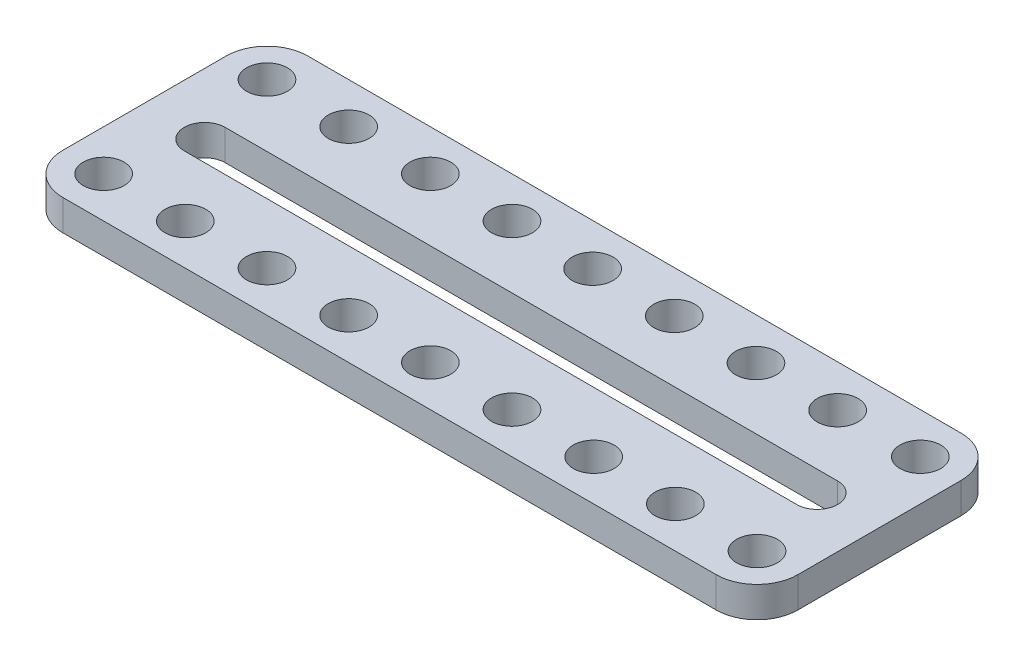
SolidWorks part; units mm, degrees
other "Markup1"
sketch "Sketch2" plane through (-43.3579, 0, 0.181) normal (0, 1, 0) x (1, 0, 0)
material "6061 Alloy"
ref_plane "前视基准面" through (0, 0, 0) normal (0, 0, 1) x (1, 0, 0)
ref_plane "上视基准面" through (0, 0, 0) normal (0, 1, 0) x (1, 0, 0)
ref_plane "右视基准面" through (0, 0, 0) normal (1, 0, 0) x (0, 0, -1)
other "Configuration Table"
sketch "Sketch11" plane through (0, 0, 0) normal (0, 1, 0) x (1, 0, 0)
  line L0 (-55.7524, -4.8796) -> (-55.7524, -20.8796)
  line L1 (-51.7524, -24.8796) -> (12.2476, -24.8796)
  line L2 (16.2476, -20.8796) -> (16.2476, -4.8796)
  line L3 (12.2476, -0.8796) -> (-51.7524, -0.8796)
  arc A0 (12.2476, -24.8796) -> (16.2476, -20.8796) centre (12.2476, -20.8796) ccw
  arc A1 (16.2476, -4.8796) -> (12.2476, -0.8796) centre (12.2476, -4.8796) ccw
  arc A2 (-55.7524, -20.8796) -> (-51.7524, -24.8796) centre (-51.7524, -20.8796) ccw
  arc A3 (-55.7524, -4.8796) -> (-51.7524, -0.8796) centre (-51.7524, -4.8796) cw
  dimension "D1" = 4
sketch "Sketch12" plane through (0, 0, 0) normal (0, 1, 0) x (1, 0, 0)
  line L0 (10.2476, -12.9827) -> (-49.7524, -12.9827) construction
  line L1 (10.2476, -14.9827) -> (-49.7524, -14.9827)
  line L2 (10.2476, -10.9827) -> (-49.7524, -10.9827)
  line L3 (-55.7524, -4.8796) -> (-55.7524, -20.8796) construction
  circle A0 centre (-51.7524, -4.8796) radius 2
  circle A1 centre (-43.7524, -4.8796) radius 2
  circle A2 centre (-35.7524, -4.8796) radius 2
  circle A3 centre (-27.7524, -4.8796) radius 2
  circle A4 centre (-19.7531, -4.9827) radius 2
  circle A5 centre (-11.7531, -4.9827) radius 2
  circle A6 centre (-3.7531, -4.9827) radius 2
  circle A7 centre (4.2469, -4.9827) radius 2
  circle A8 centre (12.2476, -4.8796) radius 2
  circle A9 centre (-51.7524, -20.8796) radius 2
  circle A10 centre (-43.7524, -20.8796) radius 2
  circle A11 centre (-35.7524, -20.8796) radius 2
  circle A12 centre (-27.7524, -20.8796) radius 2
  circle A13 centre (-19.7524, -20.8796) radius 2
  circle A14 centre (-11.7524, -20.8796) radius 2
  circle A15 centre (-3.7524, -20.8796) radius 2
  circle A16 centre (4.2476, -20.8796) radius 2
  circle A17 centre (12.2476, -20.8796) radius 2
  arc A18 (10.2476, -14.9827) -> (10.2476, -10.9827) centre (10.2476, -12.9827) ccw
  arc A19 (-49.7524, -10.9827) -> (-49.7524, -14.9827) centre (-49.7524, -12.9827) ccw
  point P42 (-19.7524, -12.9827)
  dimension "D1" = 8
  dimension "D5" = 8
  dimension "D8" = 8
  dimension "D2" = 8
  dimension "D3" = 8
  dimension "D4" = 8
  dimension "D6" = 8
  dimension "D7" = 8
  dimension "D9" = 6
extrude "Boss-Extrude1" add sketch "Sketch11" along normal blind 3
extrude "Cut-Extrude1" cut sketch "Sketch12" along normal blind 11
